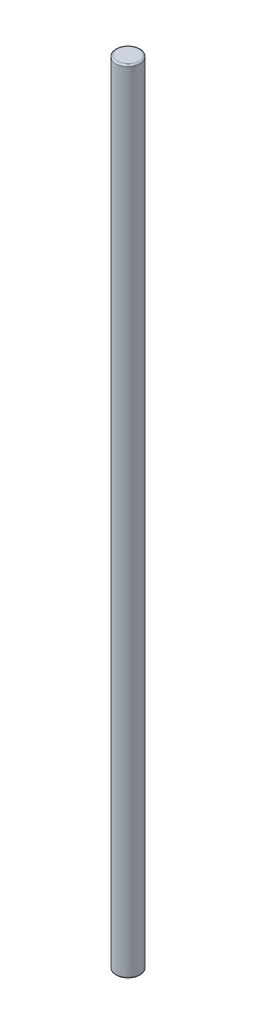
SolidWorks part; units mm, degrees
material "AISI 304"
ref_plane "Front Plane" through (0, 0, 0) normal (0, 0, 1) x (1, 0, 0)
ref_plane "Top Plane" through (0, 0, 0) normal (0, 1, 0) x (1, 0, 0)
ref_plane "Right Plane" through (0, 0, 0) normal (1, 0, 0) x (0, 0, -1)
sketch "Sketch1" plane through (0, 0, 0) normal (0, 1, 0) x (1, 0, 0)
  circle A0 centre (0, 0) radius 2
  dimension "D1" = 4
extrude "Boss-Extrude1" add sketch "Sketch1" along normal blind 130
fillet "Fillet1" radius 0.25 2 edges at (0, 0, 2) (0, 130, 2)
